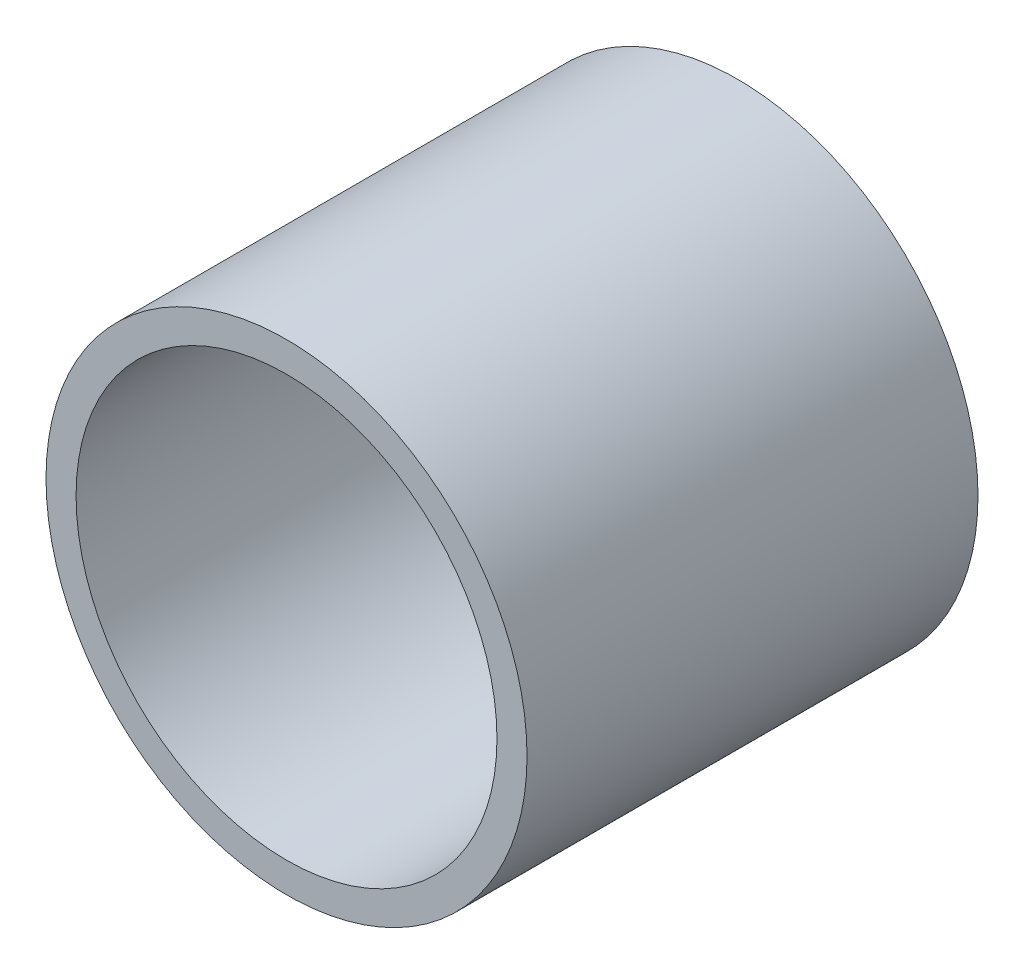
SolidWorks part; units mm, degrees
ref_plane "Front Plane" through (0, 0, 0) normal (0, 0, 1) x (1, 0, 0)
ref_plane "Top Plane" through (0, 0, 0) normal (0, 1, 0) x (1, 0, 0)
ref_plane "Right Plane" through (0, 0, 0) normal (1, 0, 0) x (0, 0, -1)
sketch "Sketch1" plane through (0, 0, 0) normal (1, 0, 0) x (0, 0, -1)
  line L0 (0.5, -0.1646) -> (1.507, -0.1646) construction
  line L2 (-1.5, 1.4354) -> (1.5, 1.4354)
  line L3 (-1.5, 1.4354) -> (-1.5, 1.2354)
  line L4 (-1.5, 1.2354) -> (1.5, 1.2354)
  line L5 (1.5, 1.4354) -> (1.5, 1.2354)
  point P7 (0, 0)
  point P8 (0, 1.2354)
  dimension "D1" = 3
  dimension "D2" = 1.4
  dimension "D3" = 1.6
revolve "Revolve1" add sketch "Sketch1" angle 360 about L0
